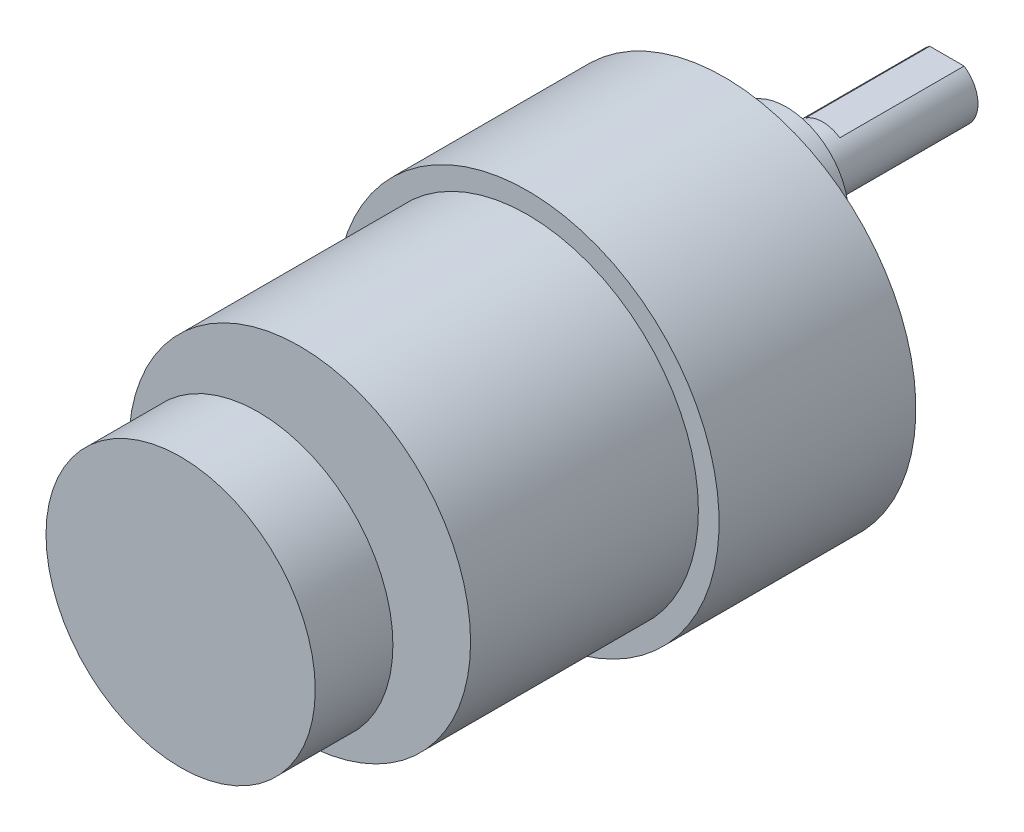
SolidWorks part; units mm, degrees
ref_plane "Front Plane" through (0, 0, 0) normal (0, 0, 1) x (1, 0, 0)
ref_plane "Top Plane" through (0, 0, 0) normal (0, 1, 0) x (1, 0, 0)
ref_plane "Right Plane" through (0, 0, 0) normal (1, 0, 0) x (0, 0, -1)
sketch "Sketch1" plane through (0, 0, 0) normal (0, 0, 1) x (1, 0, 0)
  circle A0 centre (0, 0) radius 16.5
  dimension "D1" = 33
extrude "Boss-Extrude1" add sketch "Sketch1" along normal blind 22
sketch "Sketch2" plane through (0, 0, 0) normal (0, 0, -1) x (-1, 0, 0)
  circle A0 centre (0, 0) radius 18.5
  dimension "D1" = 37
extrude "Boss-Extrude2" add sketch "Sketch2" along normal blind 19
sketch "Sketch3" plane through (0, 0, -19) normal (0, 0, -1) x (-1, 0, 0)
  circle A0 centre (0, 7) radius 6
  dimension "D1" = 12
  dimension "D2" = 7
extrude "Boss-Extrude3" add sketch "Sketch3" along normal blind 6
sketch "Sketch4" plane through (0, 0, -25) normal (0, 0, -1) x (-1, 0, 0)
  circle A0 centre (0, 7) radius 3
  dimension "D1" = 6
extrude "Boss-Extrude4" add sketch "Sketch4" along normal blind 15.5
sketch "Sketch5" plane through (0, 0, -40.5) normal (0, 0, -1) x (-1, 0, 0)
  line L0 (-1.6583, 9.5) -> (1.6583, 9.5)
  circle A1 centre (0, 7) radius 3
  circle A2 centre (0, 7) radius 3
  circle M3 centre (0, 7) radius 3
  dimension "D2" = 2.5
  dimension "D1" = 0
extrude "Cut-Extrude1" cut sketch "Sketch5" against normal blind 12 contours L0 M3
sketch "Sketch6" plane through (0, 0, -19) normal (0, 0, -1) x (-1, 0, 0)
  circle A0 centre (-15.5, 0) radius 1.5
  circle A1 centre (-7.75, 13.4234) radius 1.5
  circle A2 centre (7.75, 13.4234) radius 1.5
  circle A3 centre (15.5, 0) radius 1.5
  circle A4 centre (7.75, -13.4234) radius 1.5
  circle A5 centre (-7.75, -13.4234) radius 1.5
  point P15 (0, 0)
  dimension "D1" = 3
  dimension "D2" = 15.5
  dimension "D3" = 6
extrude "Cut-Extrude2" cut sketch "Sketch6" against normal blind 5
sketch "Sketch7" plane through (0, 0, 22) normal (0, 0, 1) x (1, 0, 0)
  circle A0 centre (0, 0) radius 13
  dimension "D1" = 26
extrude "Boss-Extrude5" add sketch "Sketch7" along normal blind 7.5 from offset 4 separate body
sketch "Sketch8" plane through (0, 0, 22) normal (0, 0, 1) x (1, 0, 0)
  line L0 (0, -20.35) -> (0, 20.35) construction
  line L1 (-6.0681, 2.5) -> (-4.0681, 2.5)
  line L2 (-6.0681, 2.5) -> (-6.0681, -2.5)
  line L3 (-6.0681, -2.5) -> (-4.0681, -2.5)
  line L4 (-4.0681, 2.5) -> (-4.0681, -2.5)
  line L5 (4.0681, 2.5) -> (4.0681, -2.5)
  line L6 (6.0681, -2.5) -> (4.0681, -2.5)
  line L7 (6.0681, 2.5) -> (6.0681, -2.5)
  line L8 (6.0681, 2.5) -> (4.0681, 2.5)
  point P4 (-4.0681, 0)
  dimension "D1" = 2
  dimension "D2" = 5
extrude "Boss-Extrude6" add sketch "Sketch8" along normal up to surface (4 mm away) up to face at (13, 0, 26)
